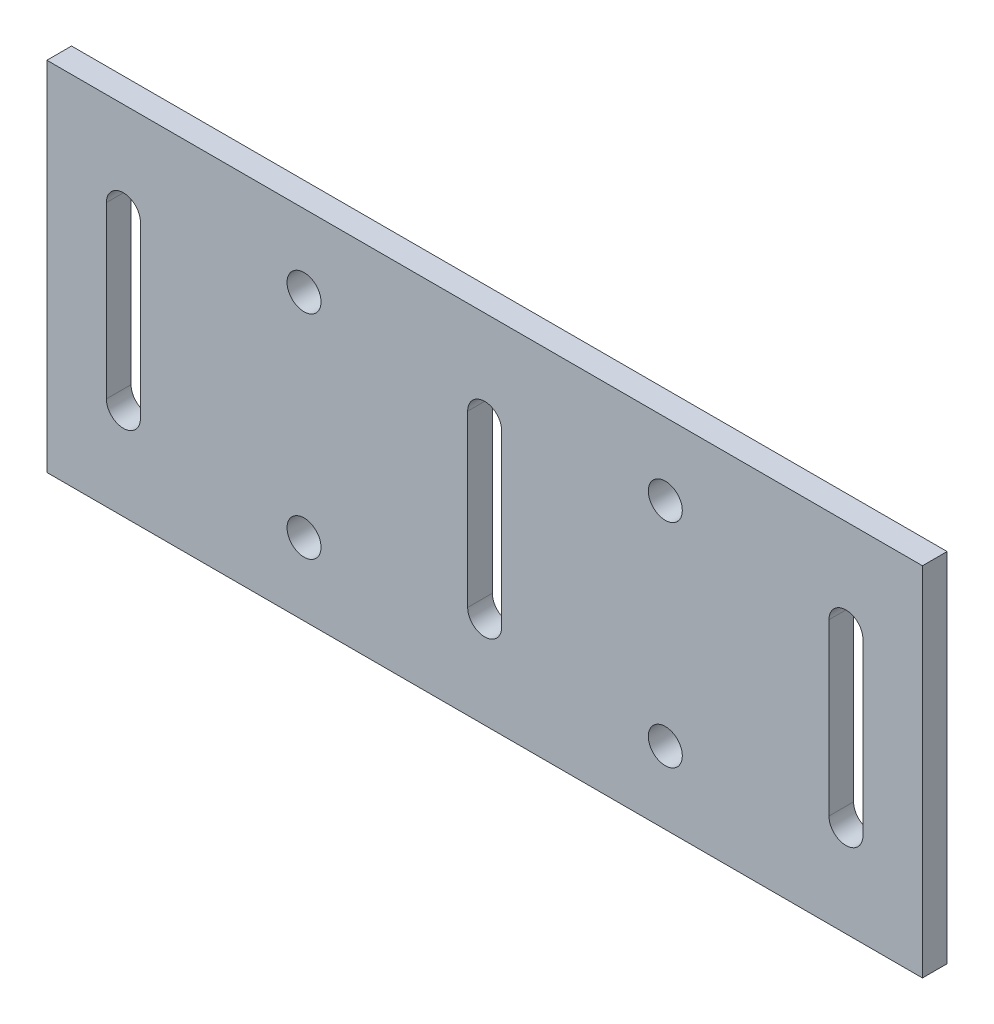
SolidWorks part; units mm, degrees
material "Бальса"
ref_plane "Спереди" through (0, 0, 0) normal (0, 0, 1) x (1, 0, 0)
ref_plane "Сверху" through (0, 0, 0) normal (0, 1, 0) x (1, 0, 0)
ref_plane "Справа" through (0, 0, 0) normal (1, 0, 0) x (0, 0, -1)
sketch "Эскиз1" plane through (0, 0, 0) normal (0, 0, 1) x (1, 0, 0)
  line L0 (18, 62) -> (18, 22) construction
  line L1 (0, 0) -> (206, 0)
  line L2 (0, 0) -> (0, 84)
  line L3 (0, 84) -> (206, 84)
  line L4 (206, 0) -> (206, 84)
  line L5 (22, 62) -> (22, 22)
  line L6 (14, 62) -> (14, 22)
  line L7 (103, 62) -> (103, 22) construction
  line L8 (107, 62) -> (107, 22)
  line L9 (99, 62) -> (99, 22)
  line L10 (188, 62) -> (188, 22) construction
  line L11 (192, 62) -> (192, 22)
  line L12 (184, 62) -> (184, 22)
  line L13 (18, 42) -> (103, 42) construction
  line L14 (103, 42) -> (188, 42) construction
  line L15 (188, 42) -> (206, 42) construction
  arc A0 (22, 62) -> (14, 62) centre (18, 62) ccw
  arc A1 (14, 22) -> (22, 22) centre (18, 22) ccw
  arc A2 (107, 62) -> (99, 62) centre (103, 62) ccw
  arc A3 (99, 22) -> (107, 22) centre (103, 22) ccw
  arc A4 (192, 62) -> (184, 62) centre (188, 62) ccw
  arc A5 (184, 22) -> (192, 22) centre (188, 22) ccw
  point P7 (18, 42)
  point P12 (103, 42)
  point P19 (188, 42)
  point P28 (206, 36.4661)
  point P31 (206, 46.2257)
  dimension "D7" = 4
  dimension "D1" = 84
  dimension "D2" = 206
  dimension "D3" = 85
  dimension "D4" = 85
  dimension "D5" = 18
  dimension "D6" = 40
extrude "Бобышка-Вытянуть1" add sketch "Эскиз1" along normal blind 5.8
sketch "Эскиз2" plane through (0, 0, 5.8) normal (0, 0, 1) x (1, 0, 0)
  line L0 (22, 42) -> (99, 42) construction
  line L1 (22, 22) -> (22, 62) construction
  line L2 (99, 62) -> (99, 22) construction
  line L3 (107, 42) -> (184, 42) construction
  line L4 (107, 22) -> (107, 62) construction
  line L5 (184, 62) -> (184, 22) construction
  line L6 (60.5, 42) -> (60.5, 67) construction
  line L7 (60.5, 67) -> (145.5, 67) construction
  line L8 (145.5, 67) -> (145.5, 42) construction
  line L9 (145.5, 42) -> (145.5, 17) construction
  line L10 (145.5, 17) -> (60.5, 17) construction
  line L11 (60.5, 17) -> (60.5, 42) construction
  circle A0 centre (60.5, 67) radius 4
  circle A1 centre (60.5, 17) radius 4
  circle A2 centre (145.5, 17) radius 4
  circle A3 centre (145.5, 67) radius 4
  dimension "D3" = 8
  dimension "D1" = 50
  dimension "D2" = 25
extrude "Вырез-Вытянуть1" cut sketch "Эскиз2" against normal up to next
